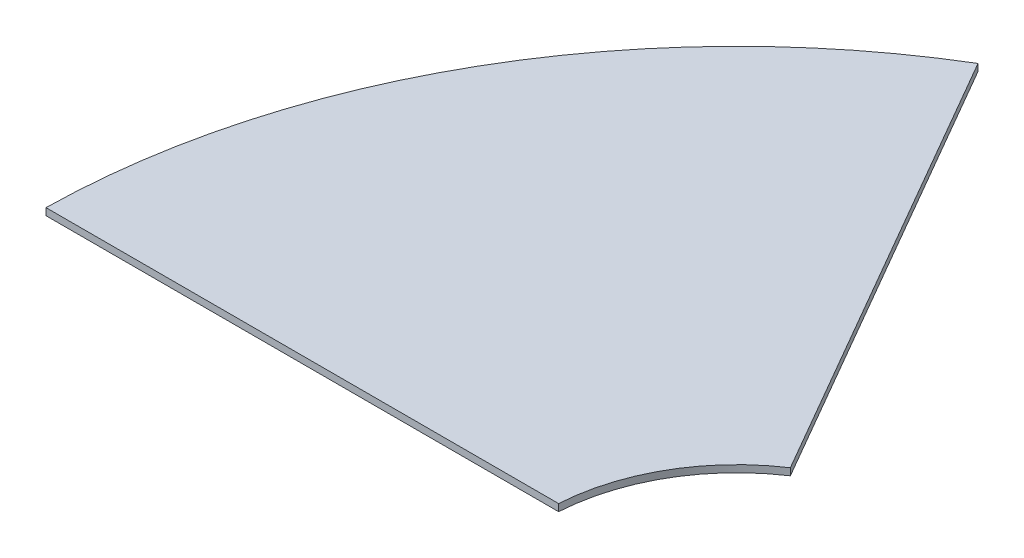
SolidWorks part; units mm, degrees
ref_plane "Front Plane" through (0, 0, 0) normal (0, 0, 1) x (1, 0, 0)
ref_plane "Top Plane" through (0, 0, 0) normal (0, 1, 0) x (1, 0, 0)
ref_plane "Right Plane" through (0, 0, 0) normal (1, 0, 0) x (0, 0, -1)
sketch "Sketch1" plane through (0, 0, 0) normal (0, 1, 0) x (1, 0, 0)
  line L0 (-152.4, 0) -> (-609.6, 0)
  line L1 (-76.2, 131.9823) -> (-304.8, 527.9291)
  line L2 (-530.4113, 300.4596) -> (-530.4291, 300.4699)
  line L3 (-525.4113, 309.1199) -> (-525.4291, 309.1301)
  line L5 (-89.7062, 135.3756) -> (-171.2603, 276.6315)
  line L6 (-162.0918, 10) -> (-325.2, 10)
  line L7 (-176.2603, 285.2917) -> (-308.4186, 514.1966)
  line L10 (-335.2, 10) -> (-599.5166, 10)
  line L14 (-89.7062, 135.3756) -> (-308.4186, 514.1966) construction
  line L15 (-176.2603, 285.2917) -> (-171.2603, 276.6315)
  line L16 (-162.0918, 10) -> (-599.5166, 10) construction
  line L17 (-335.2, 10) -> (-325.2, 10)
  arc A0 (-609.6, 0) -> (-304.8, 527.9291) centre (0, 0) cw
  arc A1 (-76.2, 131.9823) -> (-152.4, 0) centre (0, 0) ccw
  arc A2 (-599.5166, 10) -> (-521.7508, 295.4594) centre (0, 0) cw
  arc A3 (-89.7062, 135.3756) -> (-162.0918, 10) centre (0, 0) ccw
  arc A4 (-516.7508, 304.1197) -> (-308.4186, 514.1966) centre (0, 0) cw
  arc A5 (-521.7508, 295.4594) -> (-516.7508, 304.1197) centre (0, 0) cw
  arc A6 (-599.5166, 10) -> (-308.4186, 514.1966) centre (0, 0) cw construction
  point P5 (-330.2, 0)
  point P7 (0, 0)
  point P9 (-165.1, 285.9616)
  dimension "D3" = 330.2
  dimension "D1" = 609.6
  dimension "D4" = 330.2
  dimension "D5" = 10
  dimension "D2" = 2
extrude "Boss-Extrude1" add sketch "Sketch1" along normal blind 6 contours A5 A2 L10 L17 L6 A3 L5 L15 L7 A4
